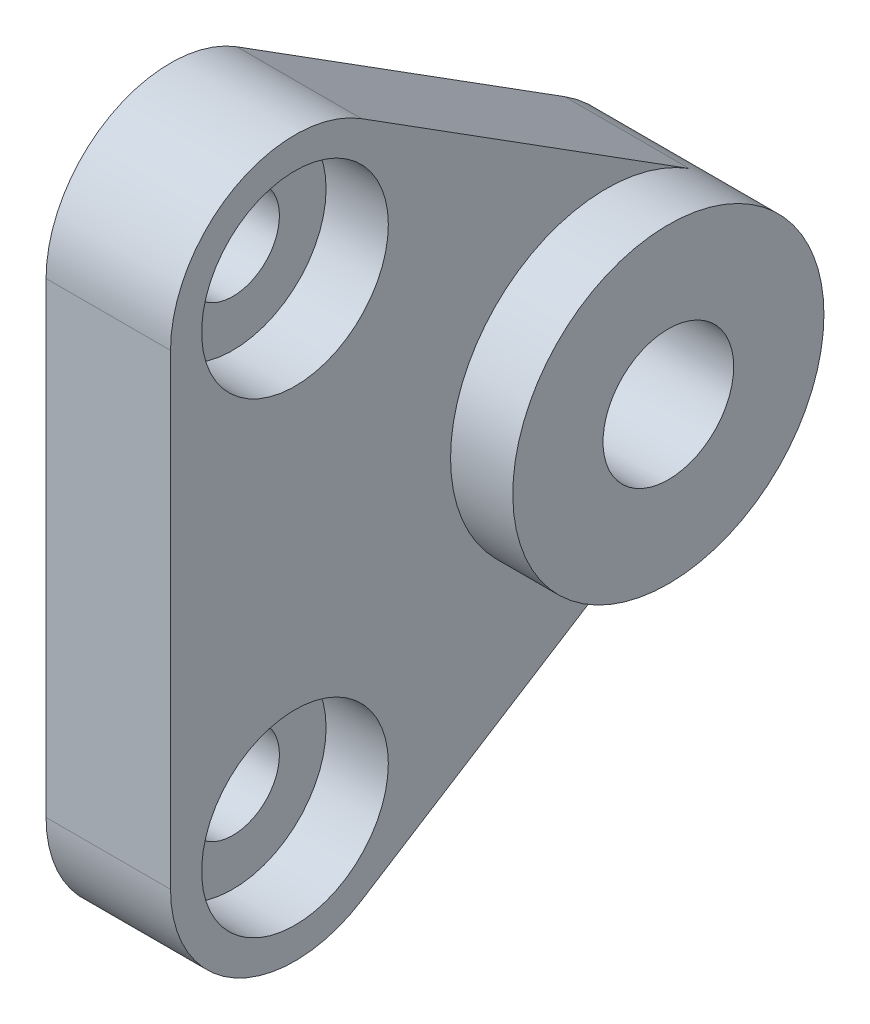
SolidWorks part; units mm, degrees
material "6061-T4 (SS)"
ref_plane "前视基准面" through (0, 0, 0) normal (0, 0, 1) x (1, 0, 0)
ref_plane "上视基准面" through (0, 0, 0) normal (0, 1, 0) x (1, 0, 0)
ref_plane "右视基准面" through (0, 0, 0) normal (1, 0, 0) x (0, 0, -1)
other "Configuration Table"
sketch "草图1" plane through (0, 0, 0) normal (1, 0, 0) x (0, 0, -1)
  line L0 (0, 0) -> (0, 15) construction
  line L1 (-4, 0) -> (-4, 15)
  line L2 (4, 0) -> (4, 15)
  line L3 (0, 7.5) -> (10, 7.5) construction
  line L4 (2.1363, 18.3817) -> (12.6704, 11.7272)
  line L5 (12.6704, 3.2728) -> (2.1363, -3.3817)
  arc A0 (-4, 0) -> (4, 0) centre (0, 0) ccw
  arc A1 (4, 15) -> (-4, 15) centre (0, 15) ccw
  circle A2 centre (0, 15) radius 1.5
  circle A3 centre (0, 0) radius 1.5
  circle A5 centre (10, 7.5) radius 2.1
  circle A6 centre (10, 7.5) radius 5
  point P3 (0, 7.5)
  dimension "D2" = 10
  dimension "D3" = 3
  dimension "D4" = 4
  dimension "D5" = 4.2
  dimension "D6" = 10
  dimension "D1" = 15
extrude "凸台-拉伸1" add sketch "草图1" along normal blind 6 contours A6 L2 A1 L1 A0 A3 A2 | A6 L4 A1 L2 | A6 L2 A5 | A6 L2 A0 L5 | L2 A6 A5
sketch "草图2" plane through (6, 0, 0) normal (1, 0, 0) x (0, 0, -1)
  circle A0 centre (0, 15) radius 3
  circle A1 centre (0, 0) radius 3
  dimension "D1" = 6
extrude "切除-拉伸1" cut sketch "草图2" against normal blind 3
sketch "草图3" plane through (3, 0, 0) normal (1, 0, 0) x (0, 0, -1)
  circle A0 centre (0, 0) radius 3 construction
  circle A1 centre (0, 15) radius 3 construction
  circle A2 centre (0, 0) radius 3
  circle A3 centre (0, 15) radius 3
extrude "切除-拉伸2" cut sketch "草图3" against normal blind 1
sketch "草图4" plane through (6, 0, 0) normal (1, 0, 0) x (0, 0, -1)
  line L3 (12.6704, 11.7272) -> (2.1363, 18.3817)
  line L4 (-4, 15) -> (-4, 0)
  line L5 (2.1363, -3.3817) -> (12.6704, 3.2728)
  line L6 (12.6704, 11.7272) -> (2.1363, 18.3817)
  line L7 (-4, 15) -> (-4, 0)
  line L8 (2.1363, -3.3817) -> (12.6704, 3.2728)
  circle A0 centre (10, 7.5) radius 5
  arc A3 (2.1363, 18.3817) -> (-4, 15) centre (0, 15) ccw
  arc A4 (-4, 0) -> (2.1363, -3.3817) centre (0, 0) ccw
  arc A5 (12.6704, 3.2728) -> (12.6704, 11.7272) centre (10, 7.5) ccw
  arc A6 (2.1363, 18.3817) -> (-4, 15) centre (0, 15) ccw
  arc A7 (-4, 0) -> (2.1363, -3.3817) centre (0, 0) ccw
  arc A8 (12.6704, 3.2728) -> (12.6704, 11.7272) centre (10, 7.5) ccw
  circle M7 centre (0, 15) radius 3
  circle M8 centre (0, 0) radius 3
  line M9 (12.6704, 11.7272) -> (2.1363, 18.3817)
  arc M10 (2.1363, 18.3817) -> (-4, 15) centre (0, 15) ccw
  line M11 (-4, 15) -> (-4, 0)
  arc M12 (-4, 0) -> (2.1363, -3.3817) centre (0, 0) ccw
  line M13 (2.1363, -3.3817) -> (12.6704, 3.2728)
  dimension "D1" = 0
extrude "切除-拉伸3" cut sketch "草图4" against normal blind 2 contours A0 M9 M10 M11 M12 M13 M8 M7
